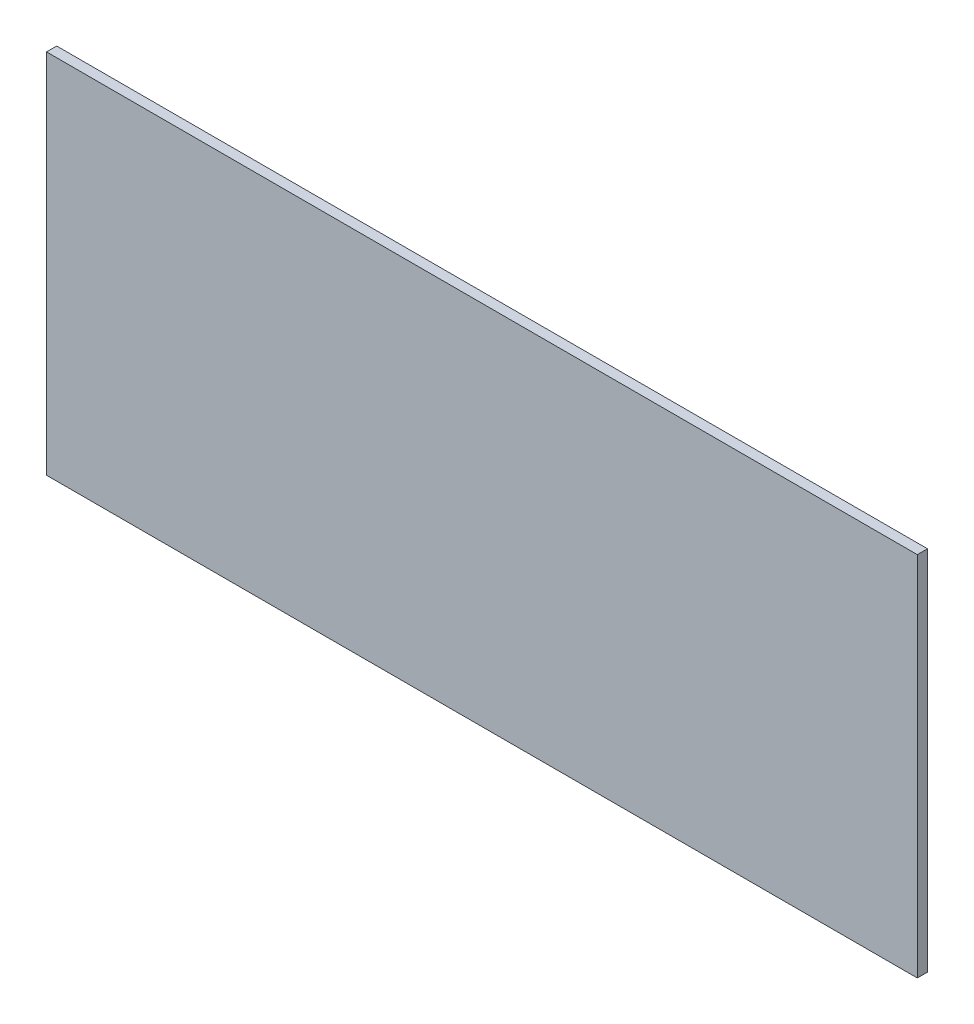
SolidWorks part; units mm, degrees
ref_plane "Front Plane" through (0, 0, 0) normal (0, 0, 1) x (1, 0, 0)
ref_plane "Top Plane" through (0, 0, 0) normal (0, 1, 0) x (1, 0, 0)
ref_plane "Right Plane" through (0, 0, 0) normal (1, 0, 0) x (0, 0, -1)
sketch "Sketch1" plane through (0, 0, 0) normal (0, 0, 1) x (1, 0, 0)
  line L1 (-84, -36) -> (87, -36)
  line L2 (-84, -36) -> (-84, 36)
  line L3 (-84, 36) -> (87, 36)
  line L4 (87, -36) -> (87, 36)
  line L5 (-84, -36) -> (87, 36) construction
  line L6 (-84, 36) -> (87, -36) construction
  point P0 (1.5, 0)
  dimension "D1" = 171
  dimension "D2" = 72
extrude "Boss-Extrude1" add sketch "Sketch1" along normal blind 2
